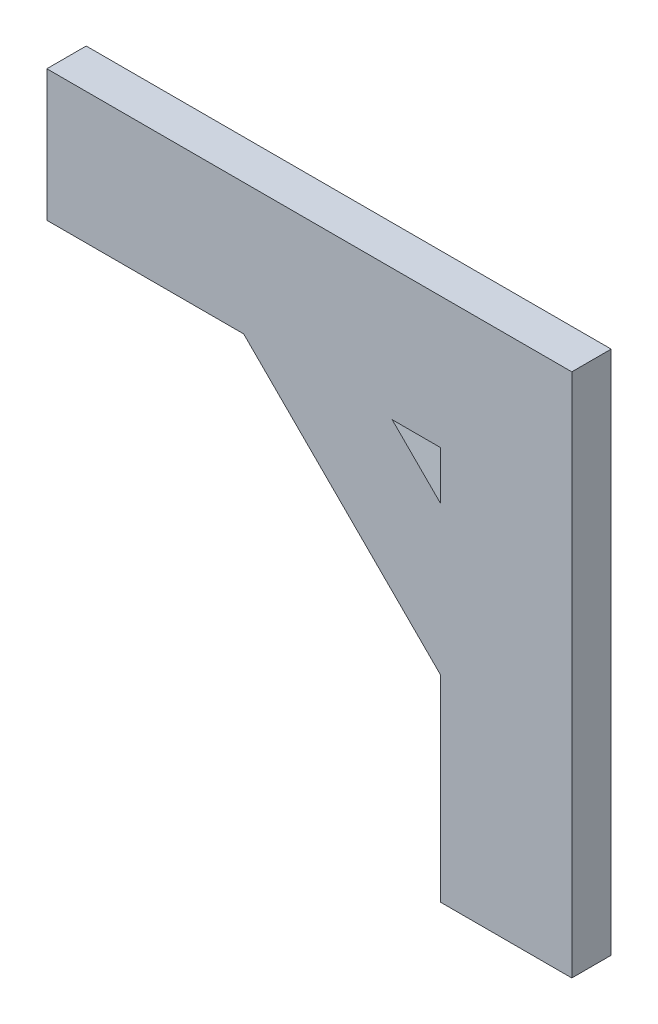
SolidWorks part; units mm, degrees
ref_plane "前基準面" through (0, 0, 0) normal (0, 0, 1) x (1, 0, 0)
ref_plane "上基準面" through (0, 0, 0) normal (0, 1, 0) x (1, 0, 0)
ref_plane "右基準面" through (0, 0, 0) normal (1, 0, 0) x (0, 0, -1)
sketch "草圖1" plane through (0, 0, 0) normal (0, 0, 1) x (1, 0, 0)
  line L0 (26.3137, -10) -> (30, -13.6863)
  line L1 (0, 0) -> (40, 0)
  line L2 (0, 0) -> (0, -10)
  line L3 (0, -10) -> (30, -10)
  line L4 (40, 0) -> (40, -10)
  line L6 (40, -10) -> (40, -40)
  line L7 (40, -40) -> (30, -40)
  line L8 (30, -10) -> (30, -40)
  line L9 (15, -10) -> (30, -25)
  dimension "D1" = 10
  dimension "D2" = 10
  dimension "D3" = 40
  dimension "D4" = 40
  dimension "D5" = 15
  dimension "D6" = 8
  dimension "D7" = 15
extrude "填料-伸長1" add sketch "草圖1" along normal blind 3 contours L3 L8 L7 L6 L4 L1 L2 | L3 L9 L8 L0
